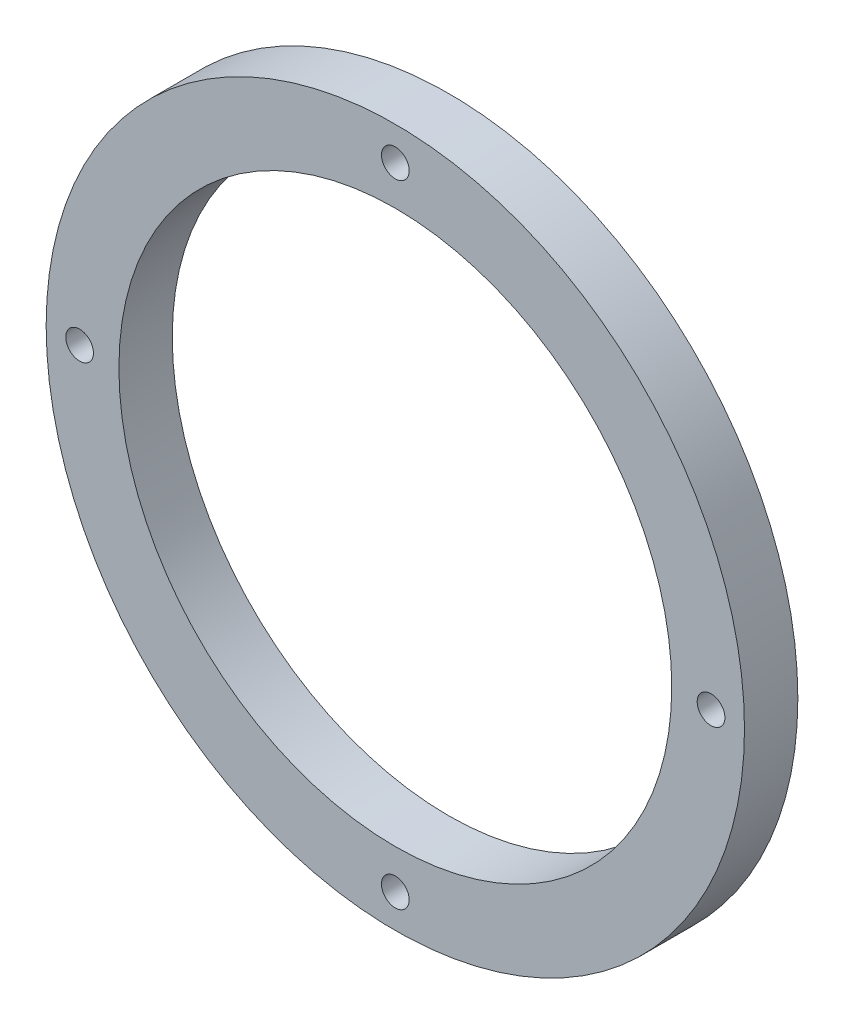
SolidWorks part; units mm, degrees
ref_plane "Front Plane" through (0, 0, 0) normal (0, 0, 1) x (1, 0, 0)
ref_plane "Top Plane" through (0, 0, 0) normal (0, 1, 0) x (1, 0, 0)
ref_plane "Right Plane" through (0, 0, 0) normal (1, 0, 0) x (0, 0, -1)
sketch "Sketch1" plane through (0, 0, 0) normal (0, 0, 1) x (1, 0, 0)
  line L0 (0, 54.25) -> (0, 0) construction
  line L1 (-54.25, 0) -> (0, 0) construction
  circle A0 centre (0, 0) radius 60
  circle A1 centre (0, 0) radius 47.5
  circle A2 centre (0, 54.25) radius 2.3812
  circle A3 centre (54.25, 0) radius 2.3812
  circle A4 centre (0, -54.25) radius 2.3812
  circle A5 centre (-54.25, 0) radius 2.3812
  point P16 (0, 0)
  dimension "D1" = 120
  dimension "D3" = 4.7625
  dimension "D4" = 54.25
  dimension "D2" = 12.5
  dimension "D5" = 4
extrude "Boss-Extrude1" add sketch "Sketch1" along normal blind 9.1694
